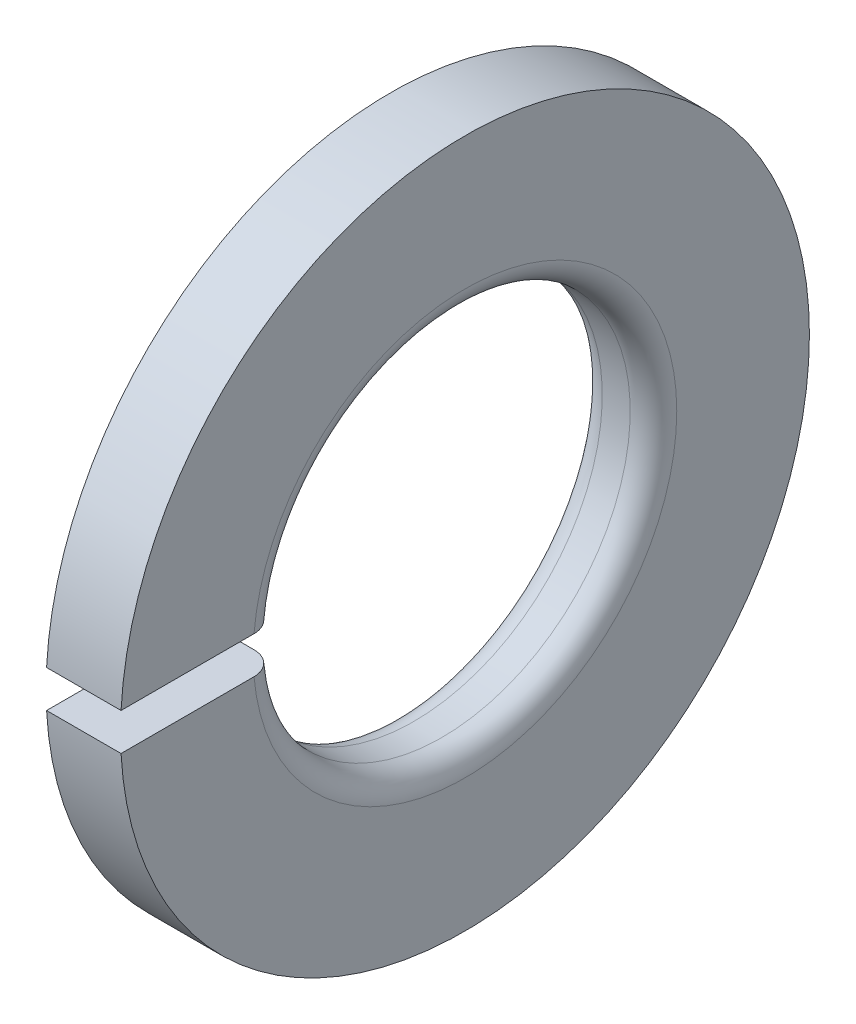
SolidWorks part; units mm, degrees
ref_plane "Plane1" through (0, 0, 0) normal (0, 0, 1) x (1, 0, 0)
ref_plane "Plane2" through (0, 0, 0) normal (0, 1, 0) x (1, 0, 0)
ref_plane "Plane3" through (0, 0, 0) normal (1, 0, 0) x (0, 0, -1)
sketch "Sketch1" plane through (0, 0, 0) normal (0, 0, 1) x (1, 0, 0)
  line L0 (-34.925, 0) -> (9.525, 0) construction
  line L1 (0, 4.55) -> (0, 7.4)
  line L2 (0, 7.4) -> (-1.6, 7.4)
  line L3 (-1.6, 7.4) -> (-1.6, 4.55)
  line L4 (-1.1, 4.05) -> (-0.5, 4.05)
  arc A0 (-1.1, 4.05) -> (-1.6, 4.55) centre (-1.1, 4.55) cw
  arc A1 (0, 4.55) -> (-0.5, 4.05) centre (-0.5, 4.55) cw
  point P8 (-1.6, 4.05)
  dimension "Fillet_rad" = 0.5
  dimension "D1" = 0.5
  dimension "Thickness" = 1.6
  dimension "Inside_dia" = 8.1
  dimension "Outside_dia" = 14.8
revolve "Base-Revolve" add sketch "Sketch1" angle 360 about L0
sketch "Sketch2" plane through (0, 0, 0) normal (-1, 0, 0) x (0, -1, 0)
  line L0 (-0.4, 0) -> (0.4, 0)
  line L1 (0, 0) -> (0, 12.7) construction
  line L2 (0.4, 0) -> (0.4, 7.548)
  line L3 (0.4, 7.548) -> (-0.4, 7.548)
  line L4 (-0.4, 7.548) -> (-0.4, 0)
  dimension "D1" = 0.8
  dimension "D2" = 7.548
extrude "Gap" cut sketch "Sketch2" along normal through all
equation "\"D1@Sketch1\" = \"Fillet_rad@Sketch1\""
equation "\"D1@Sketch2\" = \"Thickness@Sketch1\" * 0.5"
equation "\"D2@Sketch2\" = \"Outside_dia@Sketch1\" * 0.51"
